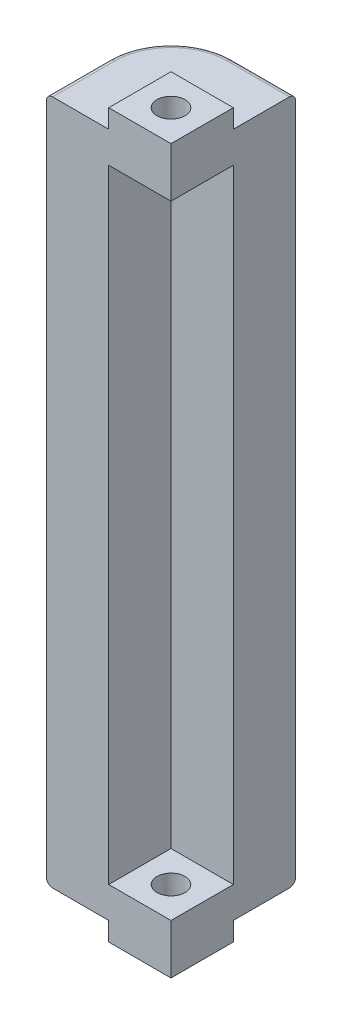
SolidWorks part; units mm, degrees
ref_plane "Front Plane" through (0, 0, 0) normal (0, 0, 1) x (1, 0, 0)
ref_plane "Top Plane" through (0, 0, 0) normal (0, 1, 0) x (1, 0, 0)
ref_plane "Right Plane" through (0, 0, 0) normal (1, 0, 0) x (0, 0, -1)
sketch "Sketch2" plane through (0, 0, 0) normal (0, 1, 0) x (1, 0, 0)
  line L0 (0, 0) -> (20, 0)
  line L1 (20, 0) -> (20, -10)
  line L2 (20, -10) -> (10, -10)
  line L3 (10, -10) -> (10, -20)
  line L4 (10, -20) -> (0, -20)
  line L5 (0, -20) -> (0, 0)
  dimension "D1" = 20
  dimension "D2" = 10
extrude "Boss-Extrude1" add sketch "Sketch2" along normal mid plane 110
sketch "Sketch3" plane through (0, 55, 0) normal (0, 1, 0) x (1, 0, 0)
  line L1 (20, -10) -> (20, 0) construction
  line L3 (0, -20) -> (10, -20) construction
  line L4 (10, -20) -> (10, -10) construction
  line L5 (10, -10) -> (20, -10) construction
  line L6 (20, -20) -> (10, -20)
  line L7 (10, -20) -> (10, -10)
  line L8 (10, -10) -> (20, -10)
  line L9 (20, -10) -> (20, -20)
  point P1 (20, -20)
  point P2 (19.8873, -20)
extrude "Boss-Extrude2" add sketch "Sketch3" along normal blind 3 and the other way blind 5 contours L6 L7 L8 L9
sketch "Sketch4" plane through (0, 50, 0) normal (0, -1, 0) x (1, 0, 0)
  point P0 (15, 15)
hole_wizard "M4 Clearance Hole1" positions "3DSketch1" profile "Sketch5" hole size "M4" standard "ANSI Metric" end condition through all
sketch3d "3DSketch1"
  point P0 (15, 50, 15)
sketch "Sketch5" plane through (15, 50, 15) normal (1, 0, 0) x (0, 0, -1)
  line L0 (0, 0) -> (0, 8)
  line L1 (0, 8) -> (2.25, 8)
  line L2 (2.25, 8) -> (2.25, 0)
  line L5 (2.25, 0) -> (0, 0)
  line L11 (0, -6.35) -> (0, 107.95) construction
  dimension "Thru Hole Dia." = 4.5
  dimension "Thru Hole Depth" = 8
mirror "Mirror1" about plane through (0, 0, 0) normal (0, 1, 0) of "M4 Clearance Hole1", "Boss-Extrude2"
fillet "Fillet2" radius 10 1 edges at (0, 0, 0)
fillet "Fillet3" radius 1 6 edges at (0, 55, 15) (2.9289, 55, 2.9289) (15, -55, 0) (2.9289, -55, 2.9289) (15, 55, 0) (0, -55, 15)
